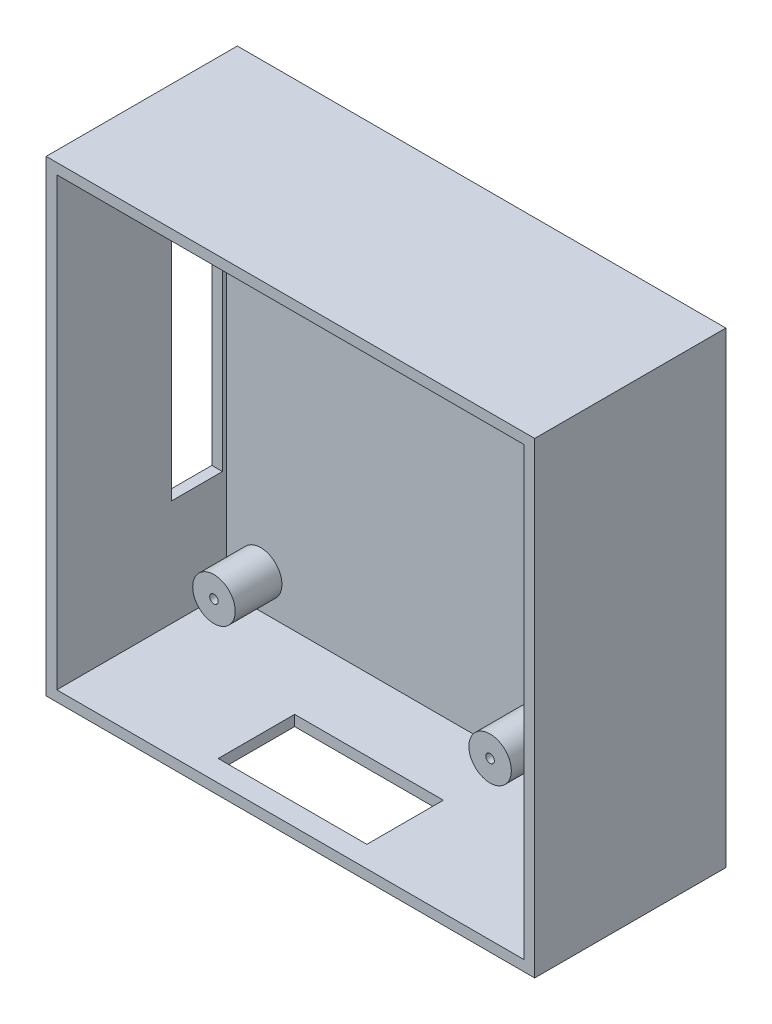
SolidWorks part; units mm, degrees
ref_plane "Front Plane" through (0, 0, 0) normal (0, 0, 1) x (1, 0, 0)
ref_plane "Top Plane" through (0, 0, 0) normal (0, 1, 0) x (1, 0, 0)
ref_plane "Right Plane" through (0, 0, 0) normal (1, 0, 0) x (0, 0, -1)
sketch "Sketch1" plane through (0, 0, 0) normal (0, 0, 1) x (1, 0, 0)
  line L19 (-57.5, 55) -> (57.5, 55)
  line L20 (-57.5, 55) -> (-57.5, -55)
  line L21 (-57.5, -55) -> (57.5, -55)
  line L22 (57.5, 55) -> (57.5, -55)
  line L23 (-57.5, 55) -> (57.5, -55) construction
  line L24 (-57.5, -55) -> (57.5, 55) construction
  point P0 (0, 0)
  point P6 (0, 0)
  dimension "D1" = 115
  dimension "D2" = 110
extrude "Boss-Extrude1" add sketch "Sketch1" along normal blind 45
sketch "Sketch2" plane through (0, 0, 45) normal (0, 0, 1) x (1, 0, 0)
  line L1 (55, 52.5) -> (-55, 52.5)
  line L2 (55, 52.5) -> (55, -52.5)
  line L3 (55, -52.5) -> (-55, -52.5)
  line L4 (-55, 52.5) -> (-55, -52.5)
  line L5 (55, 52.5) -> (-55, -52.5) construction
  line L6 (55, -52.5) -> (-55, 52.5) construction
  point P0 (0, 0)
  dimension "D1" = 110
  dimension "D2" = 105
extrude "Cut-Extrude1" cut sketch "Sketch2" against normal blind 40
sketch "Sketch10" plane through (0, 0, 5) normal (0, 0, 1) x (1, 0, 0)
  line L0 (55, 52.5) -> (-55, 52.5) construction
  line L1 (-55, 52.5) -> (-55, -52.5) construction
  line L2 (-47, 44.5) -> (18, 44.5)
  line L3 (-47, 44.5) -> (-47, -44.5)
  line L4 (-47, -44.5) -> (18, -44.5)
  line L5 (18, 44.5) -> (18, -44.5)
  line L6 (-47, 44.5) -> (18, -44.5) construction
  line L7 (-47, -44.5) -> (18, 44.5) construction
  circle A0 centre (-47, -44.5) radius 5
  circle A1 centre (18, -44.5) radius 5
  circle A2 centre (-47, 44.5) radius 5
  circle A3 centre (18, 44.5) radius 5
  point P0 (-14.5, 0)
  point P4 (-14.5, 0)
  point P15 (13, -44.5)
  point P16 (-47, 32.5)
  point P17 (-22, -44.5)
  point P20 (-47, 32.5)
  dimension "D5" = 40
  dimension "D7" = 12
  dimension "D1" = 8
  dimension "D2" = 52.5
  dimension "D3" = 65
  dimension "D4" = 89
  dimension "D6" = 35
extrude "Boss-Extrude4" add sketch "Sketch10" along normal blind 11 contours A2 | A3 | A1 | A0
sketch "Sketch11" plane through (0, 0, 16) normal (0, 0, 1) x (1, 0, 0)
  circle A0 centre (-47, 44.5) radius 1
  circle A1 centre (18, 44.5) radius 1
  circle A2 centre (18, -44.5) radius 1
  circle A3 centre (-47, -44.5) radius 1
extrude "Cut-Extrude8" cut sketch "Sketch11" against normal through all
sketch "Sketch14" plane through (0, -55, 0) normal (0, -1, 0) x (1, 0, 0)
  line L0 (-57.5, 45) -> (-57.5, 0) construction
  line L1 (-57.5, 0) -> (57.5, 0) construction
  line L3 (-22, 40) -> (13, 40)
  line L4 (-22, 40) -> (-22, 22)
  line L5 (-22, 22) -> (13, 22)
  line L6 (13, 40) -> (13, 22)
  point P0 (-22, 22)
  point P3 (13, 22)
  point P6 (-22, 40)
  dimension "D1" = 35.5
  dimension "D2" = 35
  dimension "D3" = 22
  dimension "D4" = 22
  dimension "D5" = 18
  dimension "D6" = 18
extrude "Cut-Extrude9" cut sketch "Sketch14" against normal up to next
sketch "Sketch16" plane through (-57.5, 0, 0) normal (-1, 0, 0) x (0, 0, 1)
  line L0 (45, 55) -> (0, 55) construction
  line L2 (0, 55) -> (0, -55) construction
  line L3 (6, 32.5) -> (18, 32.5)
  line L4 (6, 32.5) -> (6, -27.5)
  line L5 (6, -27.5) -> (18, -27.5)
  line L6 (18, 32.5) -> (18, -27.5)
  point P0 (6, 32.5)
  point P3 (0, 0)
  point P10 (0, 0)
  dimension "D1" = 22.5
  dimension "D2" = 6
  dimension "D4" = 60
  dimension "D5" = 12
extrude "Cut-Extrude10" cut sketch "Sketch16" against normal blind 5
